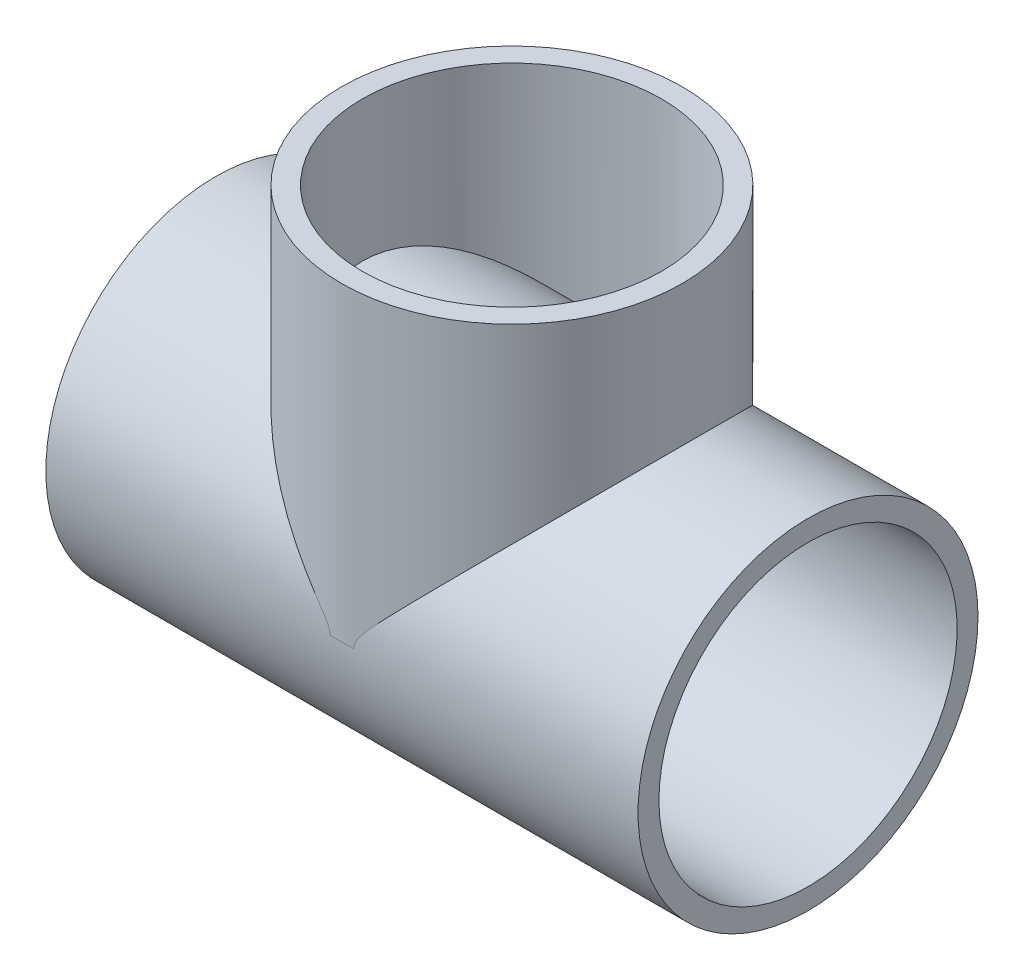
SolidWorks part; units mm, degrees
ref_plane "Front" through (0, 0, 0) normal (0, 0, 1) x (1, 0, 0)
ref_plane "Top" through (0, 0, 0) normal (0, 1, 0) x (1, 0, 0)
ref_plane "Right" through (0, 0, 0) normal (1, 0, 0) x (0, 0, -1)
sketch "Croquis1" plane through (0, 0, 0) normal (1, 0, 0) x (0, 0, -1)
  circle A0 centre (0, 0) radius 57.15
  circle A1 centre (0, 0) radius 65.15
  dimension "D1" = 114.3
  dimension "D2" = 8
extrude "Saliente-Extruir1" add sketch "Croquis1" along normal blind 227
sketch "Croquis2" plane through (0, 0, 0) normal (0, 1, 0) x (1, 0, 0)
  line L0 (0, 0) -> (227, 0) construction
  line L1 (227, -65.15) -> (227, 65.15) construction
  circle A0 centre (113.5, 0) radius 57.3088
  circle A1 centre (113.5, 0) radius 65.3088
  dimension "D1" = 8
extrude "Saliente-Extruir2" add sketch "Croquis2" along normal blind 119
sketch "Croquis3" plane through (0, 0, 0) normal (-1, 0, 0) x (0, 0, 1)
  circle A0 centre (0, 0) radius 57.15
extrude "Cortar-Extruir1" cut sketch "Croquis3" against normal up to surface (227 mm away) up to face at (227, 0, -65.15)
